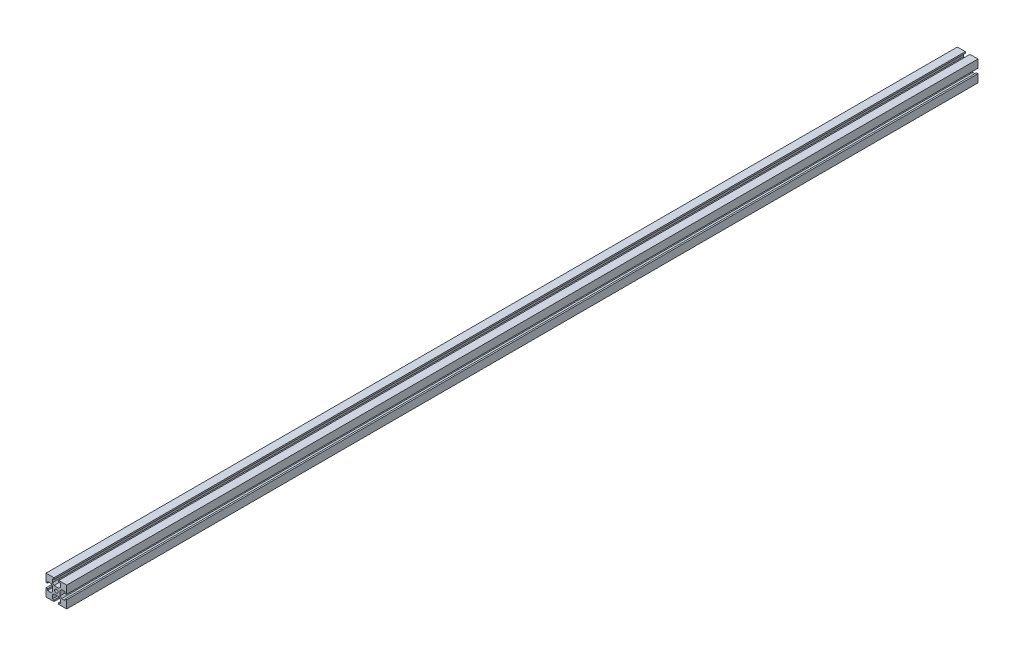
SolidWorks part; units mm, degrees
ref_plane "正面" through (0, 0, 0) normal (0, 0, 1) x (1, 0, 0)
ref_plane "平面" through (0, 0, 0) normal (0, 1, 0) x (1, 0, 0)
ref_plane "右側面" through (0, 0, 0) normal (1, 0, 0) x (0, 0, -1)
sketch "ｽｹｯﾁ2" plane through (0, 0, 0) normal (0, 0, 1) x (1, 0, 0)
  line L0 (0, 0) -> (0, 7.5) construction
  line L1 (-7.5, -7.5) -> (7.5, -7.5) construction
  line L2 (-7.5, -7.5) -> (-7.5, 7.5) construction
  line L3 (-7.5, 7.5) -> (7.5, 7.5) construction
  line L4 (7.5, -7.5) -> (7.5, 7.5) construction
  line L5 (-7.5, -7.5) -> (7.5, 7.5) construction
  line L6 (-7.5, 7.5) -> (7.5, -7.5) construction
  line L8 (1.7, 2.65) -> (-1.7, 2.65)
  line L9 (-2.85, 3.8) -> (2.85, 3.8) construction
  line L10 (-2.85, 6.4) -> (-2.85, 3.8)
  line L11 (2.85, 6.4) -> (2.85, 3.8)
  line L12 (-2.85, 3.8) -> (-1.7, 2.65)
  line L13 (1.7, 2.65) -> (2.85, 3.8)
  line L14 (-2.85, 6.4) -> (-1.7, 6.4)
  line L15 (-1.7, 6.4) -> (-1.7, 7.5)
  line L16 (-1.7, 7.5) -> (-7.5, 7.5)
  line L17 (2.85, 6.4) -> (1.7, 6.4)
  line L18 (1.7, 6.4) -> (1.7, 7.5)
  line L19 (1.7, 7.5) -> (7.5, 7.5)
  line L20 (3.8, 2.85) -> (2.65, 1.7)
  line L21 (2.65, -1.7) -> (2.65, 1.7)
  line L22 (2.65, -1.7) -> (3.8, -2.85)
  line L23 (6.4, -2.85) -> (6.4, -1.7)
  line L24 (6.4, -2.85) -> (3.8, -2.85)
  line L25 (6.4, -1.7) -> (7.5, -1.7)
  line L26 (7.5, -1.7) -> (7.5, -7.5)
  line L27 (6.4, 1.7) -> (7.5, 1.7)
  line L28 (7.5, 1.7) -> (7.5, 7.5)
  line L29 (6.4, 2.85) -> (6.4, 1.7)
  line L30 (6.4, 2.85) -> (3.8, 2.85)
  line L31 (2.85, -3.8) -> (1.7, -2.65)
  line L32 (-1.7, -2.65) -> (1.7, -2.65)
  line L33 (-1.7, -2.65) -> (-2.85, -3.8)
  line L34 (-2.85, -6.4) -> (-1.7, -6.4)
  line L35 (-2.85, -6.4) -> (-2.85, -3.8)
  line L36 (-1.7, -6.4) -> (-1.7, -7.5)
  line L37 (-1.7, -7.5) -> (-7.5, -7.5)
  line L38 (1.7, -6.4) -> (1.7, -7.5)
  line L39 (1.7, -7.5) -> (7.5, -7.5)
  line L40 (2.85, -6.4) -> (1.7, -6.4)
  line L41 (2.85, -6.4) -> (2.85, -3.8)
  line L42 (-3.8, -2.85) -> (-2.65, -1.7)
  line L43 (-2.65, 1.7) -> (-2.65, -1.7)
  line L44 (-2.65, 1.7) -> (-3.8, 2.85)
  line L45 (-6.4, 2.85) -> (-6.4, 1.7)
  line L46 (-6.4, 2.85) -> (-3.8, 2.85)
  line L47 (-6.4, 1.7) -> (-7.5, 1.7)
  line L48 (-7.5, 1.7) -> (-7.5, 7.5)
  line L49 (-6.4, -1.7) -> (-7.5, -1.7)
  line L50 (-7.5, -1.7) -> (-7.5, -7.5)
  line L51 (-6.4, -2.85) -> (-6.4, -1.7)
  line L52 (-6.4, -2.85) -> (-3.8, -2.85)
  circle A0 centre (0, 0) radius 1.25
  point P0 (0, 0)
  point P11 (0, 7.5)
  point P14 (0, 2.65)
  point P17 (0, 3.8)
  dimension "D8" = 2.5
  dimension "D1" = 15
  dimension "D2" = 3.4
  dimension "D3" = 1.1
  dimension "D4" = 2.6
  dimension "D5" = 5.7
  dimension "D6" = 3.4
  dimension "D7" = 4
extrude "ﾎﾞｽ - 押し出し1" add sketch "ｽｹｯﾁ2" along normal blind 660
